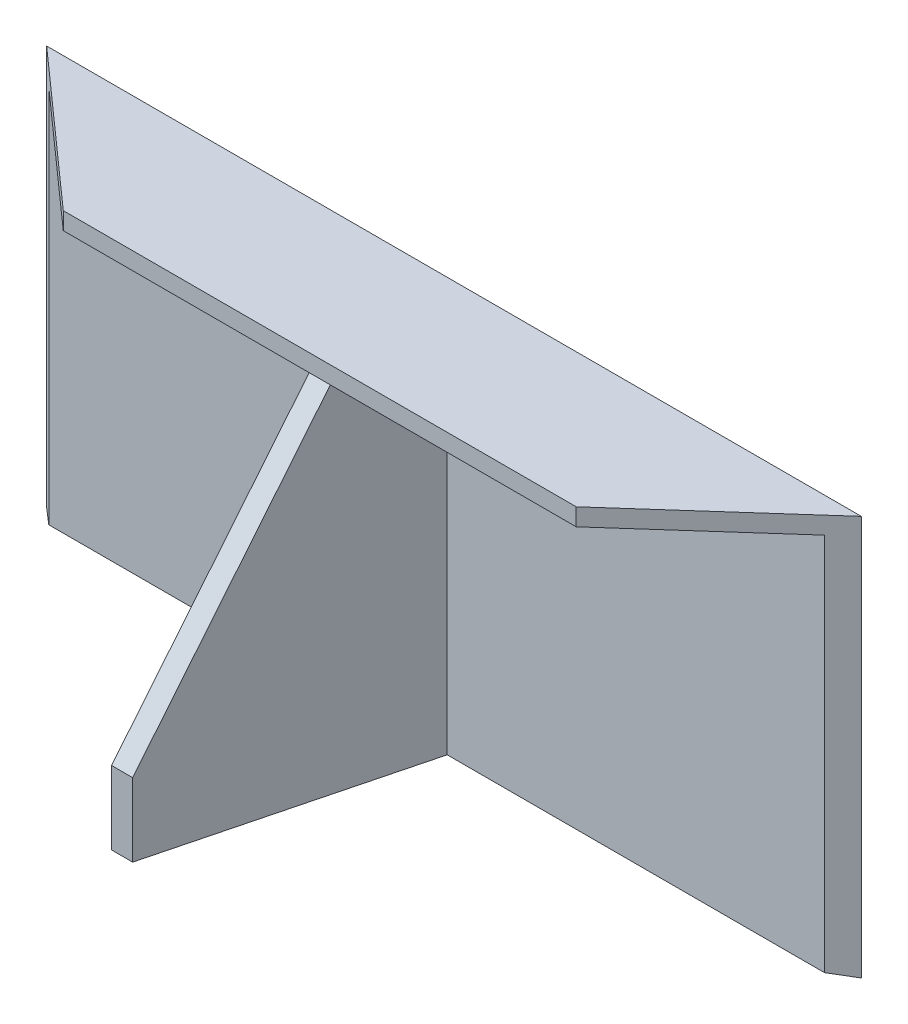
SolidWorks part; units mm, degrees
ref_plane "前视" through (0, 0, 0) normal (0, 0, 1) x (1, 0, 0)
ref_plane "上视" through (0, 0, 0) normal (0, 1, 0) x (1, 0, 0)
ref_plane "右视" through (0, 0, 0) normal (1, 0, 0) x (0, 0, -1)
sketch "草图1" plane through (0, 0, 0) normal (0, 0, 1) x (1, 0, 0)
  line L0 (270, 425.0457) -> (270, -284.5347) construction
  line L1 (0, 0) -> (540, 0)
  line L2 (0, 0) -> (0, 265)
  line L3 (0, 265) -> (540, 265)
  line L4 (540, 0) -> (540, 265)
  line L5 (270, 281) -> (-106.4291, -95.4291) construction
  line L6 (230, 208.0498) -> (230, 33.9502) construction
  line L7 (270, 147.3) -> (40.8974, 51.8974) construction
  point P7 (270, 281)
  dimension "D1" = 265
  dimension "D2" = 540
  dimension "D3" = 16
  dimension "D4" = 45
  dimension "D8" = 40
extrude "基体-拉伸" add sketch "草图1" along normal blind 11.5
sketch "草图2" plane through (0, 0, 11.5) normal (0, 0, 1) x (1, 0, 0)
  line L1 (540, 0) -> (540, 265) construction
  line L2 (0, 265) -> (540, 265)
  line L3 (0, 265) -> (0, 253.5)
  line L4 (0, 253.5) -> (540, 253.5)
  line L5 (540, 265) -> (540, 253.5)
  dimension "D1" = 11.5
extrude "凸台-拉伸1" add sketch "草图2" along normal blind 77.5
sketch "草图3" plane through (0, 265, 0) normal (0, 1, 0) x (-1, 0, 0)
  line L0 (-540, 89) -> (0, 89) construction
  line L1 (0, 89) -> (0, 0) construction
  line L2 (-270, -68.7135) -> (-270, 185.0878) construction
  line L3 (-540, 89) -> (-540, 0) construction
  line L4 (0, 0) -> (-100, 89)
  line L5 (-540, 0) -> (-440, 89)
  line L6 (0, 0) -> (0, 89)
  line L7 (0, 89) -> (-100, 89)
  line L8 (-540, 89) -> (-440, 89)
  line L9 (-540, 0) -> (-540, 89)
  point P0 (-100, 89)
  dimension "D1" = 100
extrude "切除-拉伸1" cut sketch "草图3" against normal through all
sketch "草图5" plane through (0, 0, 11.5) normal (0, 0, 1) x (1, 0, 0)
  line L0 (270, 315.5409) -> (270, -66.9152) construction
  line L1 (527.0787, 0) -> (527.0787, 253.5) construction
  line L2 (12.9213, 253.5) -> (12.9213, 0) construction
  line L3 (100, 253.5) -> (440, 253.5) construction
  line L4 (263, 253.5) -> (277, 253.5)
  line L5 (263, 253.5) -> (263, 0)
  line L6 (263, 0) -> (277, 0)
  line L7 (277, 253.5) -> (277, 0)
  line L8 (12.9213, 0) -> (527.0787, 0) construction
  dimension "D1" = 14
extrude "凸台-拉伸2" add sketch "草图5" along normal blind 208.5
sketch "草图6" plane through (277, 0, 0) normal (1, 0, 0) x (0, 0, -1)
  line L0 (45, 281) -> (45, -17.4312) construction
  line L1 (0, 0) -> (0, 265) construction
  line L2 (0, 265) -> (-89, 265) construction
  line L3 (45, 281) -> (-517.5, -219) construction
  line L4 (-220, 0) -> (-220, 253.5) construction
  line L5 (-89, 253.5) -> (-220, 93.5)
  line L6 (-220, 93.5) -> (-220, 253.5)
  line L7 (-220, 253.5) -> (-89, 253.5)
  line L8 (-175.4857, 85.0127) -> (115.3784, 198.8898) construction
  line L13 (-220, 0) -> (-11.5, 0) construction
  line L14 (-220, 45) -> (0, 0)
  line L15 (0, 0) -> (-220, 0)
  line L16 (-220, 0) -> (-220, 45)
  point P4 (45, 281)
  point P13 (-220, 93.5)
  point P21 (-220, 45)
  dimension "D1" = 45
  dimension "D2" = 16
  dimension "D3" = 562.5
  dimension "D7" = 160
  dimension "D8" = 45
  dimension "D9" = 21.381
  dimension "D11" = 500
extrude "切除-拉伸3" cut sketch "草图6" against normal through all
sketch "草图7" plane through (277, 0, 0) normal (-1, 0, 0) x (0, 0, 1)
  line L0 (0, 0) -> (11.5, 2.3523)
  line L1 (11.5, 2.3523) -> (11.5, 0)
  line L2 (11.5, 0) -> (0, 0)
extrude "切除-拉伸4" cut sketch "草图7" against normal through all
